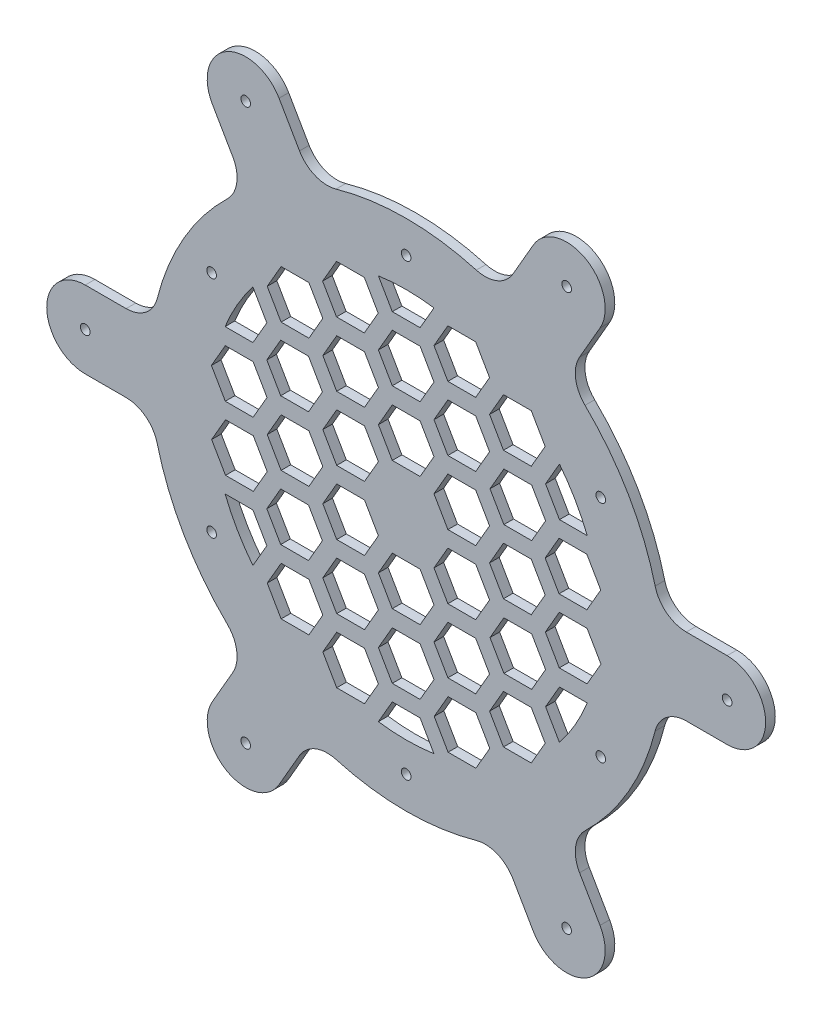
SolidWorks part; units mm, degrees
ref_plane "Front Plane" through (0, 0, 0) normal (0, 0, 1) x (1, 0, 0)
ref_plane "Top Plane" through (0, 0, 0) normal (0, 1, 0) x (1, 0, 0)
ref_plane "Right Plane" through (0, 0, 0) normal (1, 0, 0) x (0, 0, -1)
sketch "Sketch1" plane through (0, 0, 0) normal (0, 0, 1) x (1, 0, 0)
  line L0 (-561.3531, -948.2921) -> (24438.6469, 42352.9781) construction
  line L1 (-540.4731, -960.1269) -> (24459.5269, 42341.1433) construction
  line L2 (460.2716, -773.2137) -> (-24539.7284, 42528.0564) construction
  line L3 (439.0754, -784.5009) -> (-24560.9246, 42516.7693) construction
  line L4 (898.9248, 12) -> (-49101.0752, 12) construction
  line L5 (900.72, -12) -> (-49099.28, -12) construction
  line L6 (-54.0272, 69.5778) -> (-60.3923, 80.6025)
  line L7 (-33.2425, 81.5778) -> (-39.6077, 92.6025)
  line L8 (33.2425, 81.5778) -> (39.6077, 92.6025)
  line L9 (54.0272, 69.5778) -> (60.3923, 80.6025)
  line L10 (87.2697, 12) -> (100, 12)
  line L11 (87.2697, -12) -> (100, -12)
  line L12 (54.0272, -69.5778) -> (60.3923, -80.6025)
  line L13 (33.2425, -81.5778) -> (39.6077, -92.6025)
  line L14 (-54.0272, -69.5778) -> (-60.3923, -80.6025)
  line L15 (-33.2425, -81.5778) -> (-39.6077, -92.6025)
  line L16 (-87.2697, 12) -> (-100, 12)
  line L17 (-87.2697, -12) -> (-100, -12)
  line L18 (-4.3301, 27.5) -> (-8.6603, 20)
  line L25 (-8.6603, 10) -> (-12.9904, 17.5)
  line L26 (-12.9904, 17.5) -> (-21.6506, 17.5)
  line L27 (-21.6506, 17.5) -> (-25.9808, 10)
  line L28 (-25.9808, 10) -> (-21.6506, 2.5)
  line L29 (-21.6506, 2.5) -> (-12.9904, 2.5)
  line L30 (-12.9904, 2.5) -> (-8.6603, 10)
  line L31 (4.3301, 27.5) -> (-4.3301, 27.5)
  line L32 (8.6603, 20) -> (4.3301, 27.5)
  line L33 (4.3301, 12.5) -> (8.6603, 20)
  line L34 (-4.3301, 12.5) -> (4.3301, 12.5)
  line L35 (-8.6603, 20) -> (-4.3301, 12.5)
  line L36 (21.6506, 17.5) -> (12.9904, 17.5)
  line L37 (25.9808, 10) -> (21.6506, 17.5)
  line L38 (21.6506, 2.5) -> (25.9808, 10)
  line L39 (12.9904, 2.5) -> (21.6506, 2.5)
  line L40 (8.6603, 10) -> (12.9904, 2.5)
  line L41 (12.9904, 17.5) -> (8.6603, 10)
  line L42 (25.9808, -10) -> (21.6506, -2.5)
  line L43 (21.6506, -17.5) -> (25.9808, -10)
  line L44 (12.9904, -17.5) -> (21.6506, -17.5)
  line L45 (8.6603, -10) -> (12.9904, -17.5)
  line L46 (12.9904, -2.5) -> (8.6603, -10)
  line L47 (21.6506, -2.5) -> (12.9904, -2.5)
  line L48 (4.3301, -27.5) -> (8.6603, -20)
  line L49 (-4.3301, -27.5) -> (4.3301, -27.5)
  line L50 (-8.6603, -20) -> (-4.3301, -27.5)
  line L51 (-4.3301, -12.5) -> (-8.6603, -20)
  line L52 (4.3301, -12.5) -> (-4.3301, -12.5)
  line L53 (8.6603, -20) -> (4.3301, -12.5)
  line L54 (-21.6506, -17.5) -> (-12.9904, -17.5)
  line L55 (-25.9808, -10) -> (-21.6506, -17.5)
  line L56 (-21.6506, -2.5) -> (-25.9808, -10)
  line L57 (-12.9904, -2.5) -> (-21.6506, -2.5)
  line L58 (-8.6603, -10) -> (-12.9904, -2.5)
  line L59 (-12.9904, -17.5) -> (-8.6603, -10)
  line L60 (-4.3301, 7.5) -> (-6.3797, 8.6833) construction
  line L61 (8.6603, 40.1493) -> (4.3301, 47.6493)
  line L62 (-26.11, 20.0746) -> (-30.4402, 27.5746)
  line L63 (-30.4402, 27.5746) -> (-39.1004, 27.5746)
  line L64 (-39.1004, 27.5746) -> (-43.4305, 20.0746)
  line L65 (-43.4305, 20.0746) -> (-39.1004, 12.5746)
  line L66 (-39.1004, 12.5746) -> (-30.4402, 12.5746)
  line L67 (-30.4402, 12.5746) -> (-26.11, 20.0746)
  line L68 (4.3301, 47.6493) -> (-4.3301, 47.6493)
  line L69 (4.3301, 32.6493) -> (8.6603, 40.1493)
  line L70 (-4.3301, 47.6493) -> (-8.6603, 40.1493)
  line L71 (-8.6603, 40.1493) -> (-4.3301, 32.6493)
  line L72 (-4.3301, 32.6493) -> (4.3301, 32.6493)
  line L73 (39.1004, 12.5746) -> (43.4305, 20.0746)
  line L74 (43.4305, 20.0746) -> (39.1004, 27.5746)
  line L75 (30.4402, 12.5746) -> (39.1004, 12.5746)
  line L76 (39.1004, 27.5746) -> (30.4402, 27.5746)
  line L77 (30.4402, 27.5746) -> (26.11, 20.0746)
  line L78 (26.11, 20.0746) -> (30.4402, 12.5746)
  line L79 (30.4402, -27.5746) -> (39.1004, -27.5746)
  line L80 (39.1004, -27.5746) -> (43.4305, -20.0746)
  line L81 (26.11, -20.0746) -> (30.4402, -27.5746)
  line L82 (43.4305, -20.0746) -> (39.1004, -12.5746)
  line L83 (39.1004, -12.5746) -> (30.4402, -12.5746)
  line L84 (30.4402, -12.5746) -> (26.11, -20.0746)
  line L85 (-8.6603, -40.1493) -> (-4.3301, -47.6493)
  line L86 (-4.3301, -47.6493) -> (4.3301, -47.6493)
  line L87 (-4.3301, -32.6493) -> (-8.6603, -40.1493)
  line L88 (4.3301, -47.6493) -> (8.6603, -40.1493)
  line L89 (8.6603, -40.1493) -> (4.3301, -32.6493)
  line L90 (4.3301, -32.6493) -> (-4.3301, -32.6493)
  line L91 (-39.1004, -12.5746) -> (-43.4305, -20.0746)
  line L92 (-43.4305, -20.0746) -> (-39.1004, -27.5746)
  line L93 (-30.4402, -12.5746) -> (-39.1004, -12.5746)
  line L94 (-39.1004, -27.5746) -> (-30.4402, -27.5746)
  line L95 (-30.4402, -27.5746) -> (-26.11, -20.0746)
  line L96 (-26.11, -20.0746) -> (-30.4402, -12.5746)
  line L97 (0, 0) -> (47.6368, 0) construction
  line L98 (-25.9808, 30) -> (-21.6506, 22.5)
  line L99 (-25.9808, 0) -> (-30.3109, 7.5)
  line L100 (-30.3109, 7.5) -> (-38.9711, 7.5)
  line L101 (-38.9711, 7.5) -> (-43.3013, 0)
  line L102 (-43.3013, 0) -> (-38.9711, -7.5)
  line L103 (-38.9711, -7.5) -> (-30.3109, -7.5)
  line L104 (-30.3109, -7.5) -> (-25.9808, 0)
  line L105 (-21.6506, 37.5) -> (-25.9808, 30)
  line L106 (-12.9904, 37.5) -> (-21.6506, 37.5)
  line L107 (-8.6603, 30) -> (-12.9904, 37.5)
  line L108 (-12.9904, 22.5) -> (-8.6603, 30)
  line L109 (-21.6506, 22.5) -> (-12.9904, 22.5)
  line L110 (12.9904, 37.5) -> (8.6603, 30)
  line L111 (21.6506, 37.5) -> (12.9904, 37.5)
  line L112 (25.9808, 30) -> (21.6506, 37.5)
  line L113 (21.6506, 22.5) -> (25.9808, 30)
  line L114 (12.9904, 22.5) -> (21.6506, 22.5)
  line L115 (8.6603, 30) -> (12.9904, 22.5)
  line L116 (38.9711, 7.5) -> (30.3109, 7.5)
  line L117 (43.3013, 0) -> (38.9711, 7.5)
  line L118 (38.9711, -7.5) -> (43.3013, 0)
  line L119 (30.3109, -7.5) -> (38.9711, -7.5)
  line L120 (25.9808, 0) -> (30.3109, -7.5)
  line L121 (30.3109, 7.5) -> (25.9808, 0)
  line L122 (25.9808, -30) -> (21.6506, -22.5)
  line L123 (21.6506, -37.5) -> (25.9808, -30)
  line L124 (12.9904, -37.5) -> (21.6506, -37.5)
  line L125 (8.6603, -30) -> (12.9904, -37.5)
  line L126 (12.9904, -22.5) -> (8.6603, -30)
  line L127 (21.6506, -22.5) -> (12.9904, -22.5)
  line L128 (-12.9904, -37.5) -> (-8.6603, -30)
  line L129 (-21.6506, -37.5) -> (-12.9904, -37.5)
  line L130 (-25.9808, -30) -> (-21.6506, -37.5)
  line L131 (-21.6506, -22.5) -> (-25.9808, -30)
  line L132 (-12.9904, -22.5) -> (-21.6506, -22.5)
  line L133 (-8.6603, -30) -> (-12.9904, -22.5)
  line L134 (-56.3563, 17.4627) -> (-60.6864, 9.9627)
  line L135 (-25.9807, -40.0746) -> (-30.3108, -32.5746)
  line L136 (-30.3108, -32.5746) -> (-38.9711, -32.5746)
  line L137 (-38.9711, -32.5746) -> (-43.3012, -40.0746)
  line L138 (-43.3012, -40.0746) -> (-38.9711, -47.5746)
  line L139 (-38.9711, -47.5746) -> (-30.3108, -47.5746)
  line L140 (-30.3108, -47.5746) -> (-25.9807, -40.0746)
  line L141 (-47.696, 17.4627) -> (-56.3563, 17.4627)
  line L142 (-43.3659, 9.9627) -> (-47.696, 17.4627)
  line L143 (-47.696, 2.4627) -> (-43.3659, 9.9627)
  line L144 (-56.3563, 2.4627) -> (-47.696, 2.4627)
  line L145 (-60.6864, 9.9627) -> (-56.3563, 2.4627)
  line L146 (-13.055, 57.5373) -> (-21.7153, 57.5373)
  line L147 (-8.7249, 50.0373) -> (-13.055, 57.5373)
  line L148 (-13.055, 42.5373) -> (-8.7249, 50.0373)
  line L149 (-21.7153, 42.5373) -> (-13.055, 42.5373)
  line L150 (-26.0454, 50.0373) -> (-21.7153, 42.5373)
  line L151 (-21.7153, 57.5373) -> (-26.0454, 50.0373)
  line L152 (43.3012, 40.0746) -> (38.9711, 47.5746)
  line L153 (38.9711, 32.5746) -> (43.3012, 40.0746)
  line L154 (30.3108, 32.5746) -> (38.9711, 32.5746)
  line L155 (25.9807, 40.0746) -> (30.3108, 32.5746)
  line L156 (30.3108, 47.5746) -> (25.9807, 40.0746)
  line L157 (38.9711, 47.5746) -> (30.3108, 47.5746)
  line L158 (56.3563, -17.4627) -> (60.6864, -9.9627)
  line L159 (47.696, -17.4627) -> (56.3563, -17.4627)
  line L160 (43.3659, -9.9627) -> (47.696, -17.4627)
  line L161 (47.696, -2.4627) -> (43.3659, -9.9627)
  line L162 (56.3563, -2.4627) -> (47.696, -2.4627)
  line L163 (60.6864, -9.9627) -> (56.3563, -2.4627)
  line L164 (13.055, -57.5373) -> (21.7153, -57.5373)
  line L165 (8.7249, -50.0373) -> (13.055, -57.5373)
  line L166 (13.055, -42.5373) -> (8.7249, -50.0373)
  line L167 (21.7153, -42.5373) -> (13.055, -42.5373)
  line L168 (26.0454, -50.0373) -> (21.7153, -42.5373)
  line L169 (21.7153, -57.5373) -> (26.0454, -50.0373)
  line L170 (-56.2917, -2.5) -> (-60.6218, -10)
  line L171 (-8.6603, -50) -> (-12.9904, -42.5)
  line L172 (-12.9904, -42.5) -> (-21.6506, -42.5)
  line L173 (-21.6506, -42.5) -> (-25.9808, -50)
  line L174 (-25.9808, -50) -> (-21.6506, -57.5)
  line L175 (-21.6506, -57.5) -> (-12.9904, -57.5)
  line L176 (-12.9904, -57.5) -> (-8.6603, -50)
  line L177 (-47.6314, -2.5) -> (-56.2917, -2.5)
  line L178 (-60.6218, -10) -> (-56.2917, -17.5)
  line L179 (-56.2917, -17.5) -> (-47.6314, -17.5)
  line L180 (-47.6314, -17.5) -> (-43.3013, -10)
  line L181 (-43.3013, -10) -> (-47.6314, -2.5)
  line L182 (-30.3109, 47.5) -> (-38.9711, 47.5)
  line L183 (-25.9808, 40) -> (-30.3109, 47.5)
  line L184 (-38.9711, 47.5) -> (-43.3013, 40)
  line L185 (-43.3013, 40) -> (-38.9711, 32.5)
  line L186 (-38.9711, 32.5) -> (-30.3109, 32.5)
  line L187 (-30.3109, 32.5) -> (-25.9808, 40)
  line L188 (25.9808, 50) -> (21.6506, 57.5)
  line L189 (21.6506, 42.5) -> (25.9808, 50)
  line L190 (21.6506, 57.5) -> (12.9904, 57.5)
  line L191 (12.9904, 57.5) -> (8.6603, 50)
  line L192 (8.6603, 50) -> (12.9904, 42.5)
  line L193 (12.9904, 42.5) -> (21.6506, 42.5)
  line L194 (56.2917, 2.5) -> (60.6218, 10)
  line L195 (47.6314, 2.5) -> (56.2917, 2.5)
  line L196 (60.6218, 10) -> (56.2917, 17.5)
  line L197 (56.2917, 17.5) -> (47.6314, 17.5)
  line L198 (47.6314, 17.5) -> (43.3013, 10)
  line L199 (43.3013, 10) -> (47.6314, 2.5)
  line L200 (30.3109, -47.5) -> (38.9711, -47.5)
  line L201 (25.9808, -40) -> (30.3109, -47.5)
  line L202 (38.9711, -47.5) -> (43.3013, -40)
  line L203 (43.3013, -40) -> (38.9711, -32.5)
  line L204 (38.9711, -32.5) -> (30.3109, -32.5)
  line L205 (30.3109, -32.5) -> (25.9808, -40)
  line L206 (-47.7607, -22.5746) -> (-56.4209, -22.5746)
  line L207 (8.6603, -60.1493) -> (4.3301, -52.6493)
  line L208 (4.3301, -52.6493) -> (-4.3301, -52.6493)
  line L209 (-4.3301, -52.6493) -> (-8.6603, -60.1493)
  line L210 (-47.7607, -37.5746) -> (-43.4305, -30.0746)
  line L211 (-43.4305, -30.0746) -> (-47.7607, -22.5746)
  line L212 (-43.4305, 30.0746) -> (-47.7607, 37.5746)
  line L213 (6.4952, -63.8993) -> (8.6603, -60.1493) [skipped]
  line L214 (-3.2651, -67.6493) -> (0, -67.6493) [skipped]
  line L215 (-6.4952, -63.8993) -> (-4.3301, -67.6493) [skipped]
  line L216 (-56.4209, 22.5746) -> (-47.7607, 22.5746)
  line L217 (-47.7607, 22.5746) -> (-43.4305, 30.0746)
  line L218 (4.3301, 52.6493) -> (8.6603, 60.1493)
  line L219 (-8.6603, 60.1493) -> (-4.3301, 52.6493)
  line L220 (-4.3301, 52.6493) -> (4.3301, 52.6493)
  line L221 (47.7607, 22.5746) -> (56.4209, 22.5746)
  line L222 (47.7607, 37.5746) -> (43.4305, 30.0746)
  line L223 (43.4305, 30.0746) -> (47.7607, 22.5746)
  line L224 (43.4305, -30.0746) -> (47.7607, -37.5746)
  line L225 (56.4209, -22.5746) -> (47.7607, -22.5746)
  line L226 (47.7607, -22.5746) -> (43.4305, -30.0746)
  circle A0 centre (0, 0) radius 100 construction
  circle A1 centre (100, 0) radius 1.5
  arc A7 (100, -12) -> (100, 12) centre (100, 0) ccw
  circle A8 centre (50, -86.6025) radius 1.5
  arc A14 (39.6077, -92.6025) -> (60.3923, -80.6025) centre (50, -86.6025) ccw
  circle A15 centre (-50, -86.6025) radius 1.5
  arc A21 (-60.3923, -80.6025) -> (-39.6077, -92.6025) centre (-50, -86.6025) ccw
  circle A22 centre (-100, 0) radius 1.5
  arc A28 (-100, 12) -> (-100, -12) centre (-100, 0) ccw
  circle A29 centre (-50, 86.6025) radius 1.5
  arc A35 (-39.6077, 92.6025) -> (-60.3923, 80.6025) centre (-50, 86.6025) ccw
  circle A36 centre (50, 86.6025) radius 1.5
  arc A42 (60.3923, 80.6025) -> (39.6077, 92.6025) centre (50, 86.6025) ccw
  arc A43 (-55.7221, 57.4025) -> (-77.5731, 19.5556) centre (0, 0) ccw
  circle A44 centre (0, 0) radius 70 construction
  circle A46 centre (0, 0) radius 20 construction
  circle A47 centre (-17.3205, 10) radius 7.5 construction
  circle A48 centre (0, 20) radius 7.5 construction
  circle A49 centre (17.3205, 10) radius 7.5 construction
  circle A50 centre (17.3205, -10) radius 7.5 construction
  circle A51 centre (0, -20) radius 7.5 construction
  arc A52 (-21.8509, -76.958) -> (21.8509, -76.958) centre (0, 0) ccw
  arc A53 (55.7221, -57.4025) -> (77.5731, -19.5556) centre (0, 0) ccw
  arc A54 (21.8509, 76.958) -> (-21.8509, 76.958) centre (0, 0) ccw
  arc A55 (-77.5731, -19.5556) -> (-55.7221, -57.4025) centre (0, 0) ccw
  arc A56 (77.5731, 19.5556) -> (55.7221, 57.4025) centre (0, 0) ccw
  circle A57 centre (0, 70) radius 1.5
  circle A58 centre (60.6218, 35) radius 1.5
  circle A59 centre (60.6218, -35) radius 1.5
  circle A60 centre (0, -70) radius 1.5
  circle A61 centre (-60.6218, -35) radius 1.5
  circle A62 centre (-60.6218, 35) radius 1.5
  circle A63 centre (-17.3205, -10) radius 7.5 construction
  circle A64 centre (0, 0) radius 40 construction
  circle A65 centre (-34.7703, 20.0746) radius 7.5 construction
  circle A66 centre (0, 40.1493) radius 7.5 construction
  circle A67 centre (34.7703, 20.0746) radius 7.5 construction
  circle A68 centre (34.7703, -20.0746) radius 7.5 construction
  circle A69 centre (0, -40.1493) radius 7.5 construction
  circle A70 centre (-34.7703, -20.0746) radius 7.5 construction
  circle A71 centre (0, 0) radius 34.641 construction
  circle A72 centre (-34.641, 0) radius 7.5 construction
  circle A73 centre (-17.3205, 30) radius 7.5 construction
  circle A74 centre (17.3205, 30) radius 7.5 construction
  circle A75 centre (34.641, 0) radius 7.5 construction
  circle A76 centre (17.3205, -30) radius 7.5 construction
  circle A77 centre (-17.3205, -30) radius 7.5 construction
  circle A78 centre (0, 0) radius 52.9714 construction
  circle A79 centre (-34.641, -40.0746) radius 7.5 construction
  circle A80 centre (-52.0261, 9.9627) radius 7.5 construction
  arc A81 (77.5731, 19.5556) -> (87.2697, 12) centre (87.2697, 22) ccw
  arc A82 (87.2697, -12) -> (77.5731, -19.5556) centre (87.2697, -22) ccw
  arc A83 (55.7221, -57.4025) -> (54.0272, -69.5778) centre (62.6874, -64.5778) ccw
  arc A84 (33.2425, -81.5778) -> (21.8509, -76.958) centre (24.5823, -86.5778) ccw
  arc A85 (-21.8509, -76.958) -> (-33.2425, -81.5778) centre (-24.5823, -86.5778) ccw
  arc A86 (-54.0272, -69.5778) -> (-55.7221, -57.4025) centre (-62.6874, -64.5778) ccw
  arc A87 (-77.5731, -19.5556) -> (-87.2697, -12) centre (-87.2697, -22) ccw
  arc A88 (-87.2697, 12) -> (-77.5731, 19.5556) centre (-87.2697, 22) ccw
  arc A89 (-54.0272, 69.5778) -> (-55.7221, 57.4025) centre (-62.6874, 64.5778) cw
  arc A90 (55.7221, 57.4025) -> (54.0272, 69.5778) centre (62.6874, 64.5778) cw
  arc A91 (33.2425, 81.5778) -> (21.8509, 76.958) centre (24.5823, 86.5778) cw
  arc A92 (-21.8509, 76.958) -> (-33.2425, 81.5778) centre (-24.5823, 86.5778) cw
  circle A93 centre (-17.3852, 50.0373) radius 7.5 construction
  circle A94 centre (34.641, 40.0746) radius 7.5 construction
  circle A95 centre (52.0261, -9.9627) radius 7.5 construction
  circle A96 centre (17.3852, -50.0373) radius 7.5 construction
  circle A97 centre (-17.3205, -50) radius 7.5 construction
  circle A98 centre (-51.9615, -10) radius 7.5 construction
  circle A99 centre (-34.641, 40) radius 7.5 construction
  circle A100 centre (17.3205, 50) radius 7.5 construction
  circle A101 centre (51.9615, 10) radius 7.5 construction
  circle A102 centre (34.641, -40) radius 7.5 construction
  circle A103 centre (0, 0) radius 60.7695 construction
  arc A104 (-8.6603, -60.1493) -> (8.6603, -60.1493) centre (0, 0) ccw
  arc A105 (7.4984, -60.3051) -> (-7.4984, -60.3051) centre (0, -60.1493) ccw construction
  arc A106 (-56.4209, -22.5746) -> (-47.7607, -37.5746) centre (0, 0) ccw
  arc A107 (-48.4766, -36.6463) -> (-55.975, -23.6588) centre (-52.0908, -30.0746) ccw construction
  arc A108 (-47.7607, 37.5746) -> (-56.4209, 22.5746) centre (0, 0) ccw
  arc A109 (-55.975, 23.6588) -> (-48.4766, 36.6463) centre (-52.0908, 30.0746) ccw construction
  arc A110 (8.6603, 60.1493) -> (-8.6603, 60.1493) centre (0, 0) ccw
  arc A111 (-7.4984, 60.3051) -> (7.4984, 60.3051) centre (0, 60.1493) ccw construction
  arc A112 (56.4209, 22.5746) -> (47.7607, 37.5746) centre (0, 0) ccw
  arc A113 (48.4766, 36.6463) -> (55.975, 23.6588) centre (52.0908, 30.0746) ccw construction
  arc A114 (47.7607, -37.5746) -> (56.4209, -22.5746) centre (0, 0) ccw
  arc A115 (55.975, -23.6588) -> (48.4766, -36.6463) centre (52.0908, -30.0746) ccw construction
  point P177 (58.7878, -12)
  point P178 (0, 0)
  point P183 (58.7878, 12)
  point P198 (-58.7878, 12)
  point P204 (-39.7862, 44.9117)
  point P207 (79.0949, 12)
  point P210 (79.0949, -12)
  point P213 (49.9397, -62.4982)
  point P216 (29.1551, -74.4982)
  point P219 (-29.1551, -74.4982)
  point P222 (-49.9397, -62.4982)
  point P225 (-79.0949, -12)
  point P228 (-79.0949, 12)
  point P231 (-49.9397, 62.4982)
  point P233 (49.9397, 62.4982)
  point P236 (29.1551, 74.4982)
  point P239 (-29.1551, 74.4982)
  point P269 (0, 0)
  point P321 (0, 0)
  point P371 (0, 0)
  point P420 (0, 0)
  point P471 (0, 0)
  dimension "D1" = 6
  dimension "D3" = 3
  dimension "D9" = 12
  dimension "D10" = 80
  dimension "D11" = 140
  dimension "D12" = 40
  dimension "D14" = 3
  dimension "D15" = 10
  dimension "D16" = 10
  dimension "D17" = 200
  dimension "D18" = 15
  dimension "D20" = 70
  dimension "D23" = 80
  dimension "D24" = 15
  dimension "D26" = 5
  dimension "D27" = 15
  dimension "D28" = 6
  dimension "D29" = 15
  dimension "D33" = 15
  dimension "D36" = 6
  dimension "D19" = 6
  dimension "D21" = 70
  dimension "D30" = 5
  dimension "D32" = 5
  dimension "D34" = 0
  dimension "D37" = 5
  dimension "D38" = 0
  dimension "D13" = 6
  dimension "D25" = 6
  dimension "D31" = 6
  dimension "D35" = 6
extrude "Boss-Extrude1" add sketch "Sketch1" along normal blind 3
